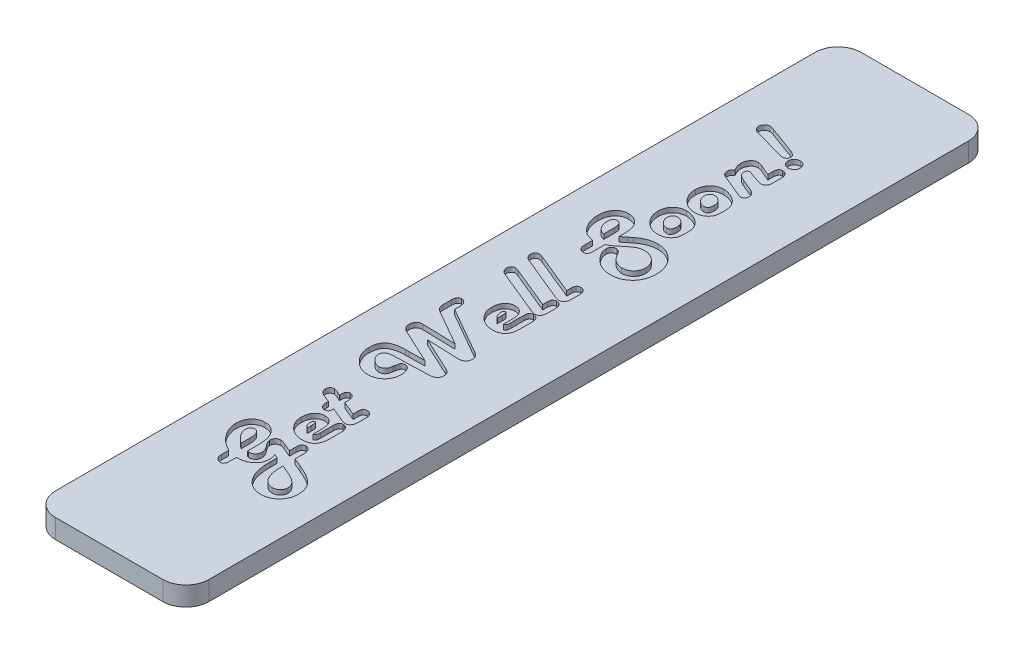
SolidWorks part; units mm, degrees
ref_plane "Front Plane" through (0, 0, 0) normal (0, 0, 1) x (1, 0, 0)
ref_plane "Top Plane" through (0, 0, 0) normal (0, 1, 0) x (1, 0, 0)
ref_plane "Right Plane" through (0, 0, 0) normal (1, 0, 0) x (0, 0, -1)
sketch "Sketch1" plane through (0, 0, 0) normal (0, 0, 1) x (1, 0, 0)
  line L0 (0, 1.5875) -> (0, -1.5875)
  line L1 (-12.7, 0) -> (12.7, 0) construction
  point P6 (0, 0)
  dimension "Width" = 25.4
  dimension "Thk" = 3.175
sketch "Sketch2" plane through (0, 0, 0) normal (1, 0, 0) x (0, 0, -1)
  line L0 (66.675, 0) -> (-66.675, 0)
  point P4 (0, 0)
  dimension "Length" = 133.35
sketch "Sketch3" plane through (0, 0, 0) normal (0, 0, 1) x (1, 0, 0)
  line L1 (12.7, 1.5875) -> (-12.7, 1.5875)
  line L2 (12.7, 1.5875) -> (12.7, -1.5875)
  line L3 (12.7, -1.5875) -> (-12.7, -1.5875)
  line L4 (-12.7, 1.5875) -> (-12.7, -1.5875)
  line L5 (12.7, 1.5875) -> (-12.7, -1.5875) construction
  line L6 (12.7, -1.5875) -> (-12.7, 1.5875) construction
  point P0 (0, 0)
extrude "Boss-Extrude1" add sketch "Sketch3" along normal up to vertex (66.675 mm away) and the other way up to vertex (66.675 mm away) up to point (0, 0, 66.675) other way up to point (0, 0, -66.675)
sketch "Sketch5" plane through (0, 1.5875, 0) normal (0, 1, 0) x (1, 0, 0)
  line L0 (-9.398, 66.929) -> (9.652, 66.929) construction
  line L1 (12.954, 63.627) -> (12.954, -63.373) construction
  line L2 (9.652, -66.675) -> (-9.398, -66.675) construction
  line L3 (-12.7, -63.373) -> (-12.7, 63.627) construction
  line L12 (12.7, -66.675) -> (12.7, 66.675)
  line L13 (12.7, 66.675) -> (-12.7, 66.675)
  line L14 (-12.7, 66.675) -> (-12.7, -66.675)
  line L15 (-12.7, -66.675) -> (12.7, -66.675)
  line L16 (12.7, -62.865) -> (12.7, 62.865)
  line L17 (8.89, 66.675) -> (-8.89, 66.675)
  line L18 (-12.7, 62.865) -> (-12.7, -62.865)
  line L19 (-8.89, -66.675) -> (8.89, -66.675)
  arc A0 (9.652, -66.675) -> (12.954, -63.373) centre (9.652, -63.373) ccw construction
  arc A1 (9.652, -66.675) -> (12.954, -63.373) centre (9.652, -63.373) ccw construction
  arc A2 (-12.7, -63.373) -> (-9.398, -66.675) centre (-9.398, -63.373) ccw construction
  arc A3 (-12.7, -63.373) -> (-9.398, -66.675) centre (-9.398, -63.373) ccw construction
  arc A4 (12.954, 63.627) -> (9.652, 66.929) centre (9.652, 63.627) ccw construction
  arc A5 (12.954, 63.627) -> (9.652, 66.929) centre (9.652, 63.627) ccw construction
  arc A6 (-9.398, 66.929) -> (-12.7, 63.627) centre (-9.398, 63.627) ccw construction
  arc A7 (-9.398, 66.929) -> (-12.7, 63.627) centre (-9.398, 63.627) ccw construction
  arc A8 (12.7, 62.865) -> (8.89, 66.675) centre (8.89, 62.865) ccw
  arc A9 (-8.89, 66.675) -> (-12.7, 62.865) centre (-8.89, 62.865) ccw
  arc A10 (12.7, -62.865) -> (8.89, -66.675) centre (8.89, -62.865) cw
  arc A11 (-8.89, -66.675) -> (-12.7, -62.865) centre (-8.89, -62.865) cw
  dimension "D2" = 3.81
  dimension "D1" = 0
extrude "Cut-Extrude2" cut sketch "Sketch5" against normal through all flip side to cut
sketch "Sketch4" plane through (0, 1.5875, 0) normal (0, 1, 0) x (1, 0, 0)
  line L0 (0, 0) -> (2.54, 0) construction
  line L1 (2.54, -66.675) -> (2.54, 66.675) construction
  line L2 (8.89, 66.675) -> (-8.89, 66.675) construction
  text T0 "Get Well Soon!" font "Harlow Solid Italic" height 10
  point P8 (2.54, 0)
  dimension "D1" = 2.54
extrude "Cut-Extrude1" cut sketch "Sketch4" against normal blind 0.7937
